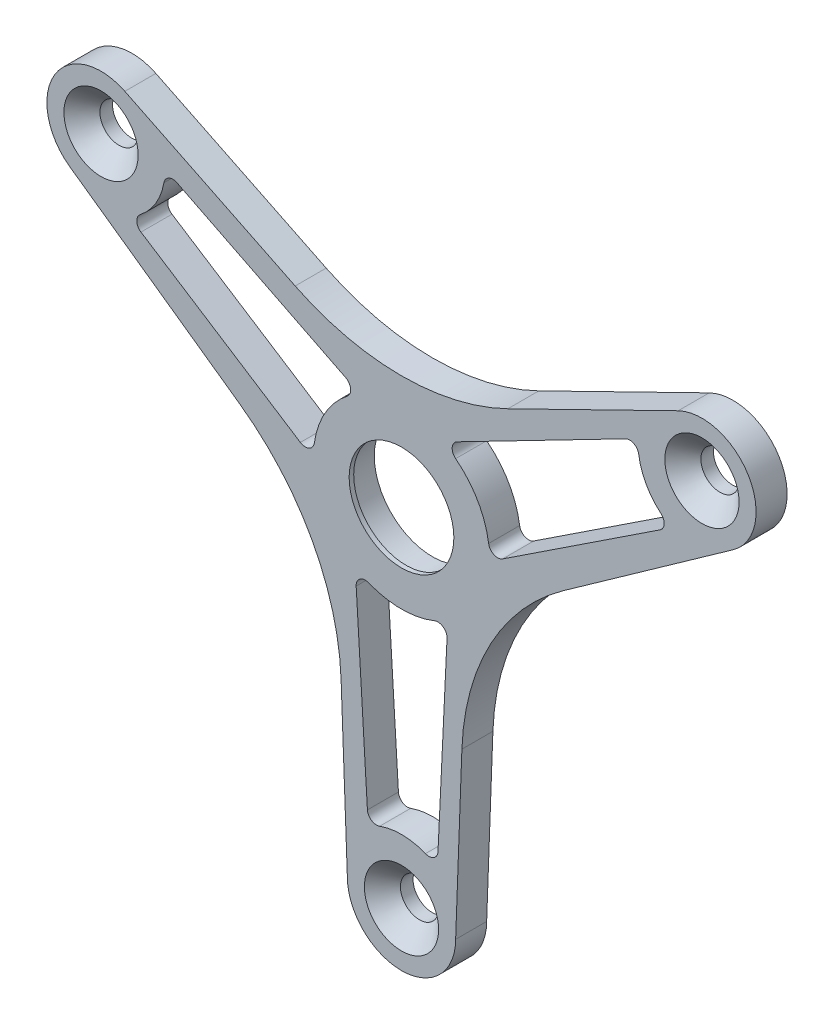
SolidWorks part; units mm, degrees
material "1060 合金"
ref_plane "前视基准面" through (0, 0, 0) normal (0, 0, 1) x (1, 0, 0)
ref_plane "上视基准面" through (0, 0, 0) normal (0, 1, 0) x (1, 0, 0)
ref_plane "右视基准面" through (0, 0, 0) normal (1, 0, 0) x (0, 0, -1)
sketch "草图1" plane through (0, 0, 0) normal (0, 0, 1) x (1, 0, 0)
  line L0 (-32.9393, 19.0175) -> (0, 0) construction
  line L1 (0, 0) -> (32.9393, 19.0175) construction
  line L2 (0, 0) -> (0, -38.035) construction
  line L3 (-30.3285, 24.3474) -> (-11.6571, 15.2016)
  line L4 (11.6571, 15.2016) -> (30.3285, 24.3474)
  line L5 (-36.371, 14.1752) -> (-17.7794, 0.9993)
  line L6 (-6.6205, -19.635) -> (-5.935, -38.035)
  line L7 (36.371, 14.1752) -> (17.7794, 0.9993)
  line L8 (6.6205, -19.635) -> (5.935, -38.035)
  circle A0 centre (0, 0) radius 5.74
  circle A1 centre (-32.9393, 19.0175) radius 2.095
  circle A2 centre (32.9393, 19.0175) radius 2.095
  circle A3 centre (0, -38.035) radius 2.095
  circle A4 centre (-32.9393, 19.0175) radius 5.935
  circle A5 centre (32.9393, 19.0175) radius 5.935
  circle A6 centre (0, -38.035) radius 5.935
  arc A7 (-11.6571, 15.2016) -> (11.6571, 15.2016) centre (0, 39) ccw
  arc A8 (-17.7794, 0.9993) -> (-6.6205, -19.635) centre (-33.1021, -20.6216) cw
  arc A9 (17.7794, 0.9993) -> (6.6205, -19.635) centre (33.1021, -20.6216) ccw
  dimension "D3" = 4.19
  dimension "D4" = 4.19
  dimension "D5" = 4.19
  dimension "D9" = 11.87
  dimension "D10" = 11.87
  dimension "D11" = 11.87
  dimension "D14" = 26.5
  dimension "D15" = 26.5
  dimension "D16" = 39
  dimension "D12" = 11.48
  dimension "D13" = 26.5
  dimension "D1" = 120
  dimension "D2" = 120
  dimension "D6" = 38.035
  dimension "D7" = 38.035
  dimension "D8" = 38.035
  dimension "D17" = 39
  dimension "D18" = 39
extrude "凸台-拉伸1" add sketch "草图1" along normal blind 3.4 contours A4 A1 | A5 A2 | A9 L7 A5 L4 A7 L3 A4 L5 A8 L6 A6 L8 A0 | A6 A3
sketch "草图2" plane through (0, 0, 3.4) normal (0, 0, 1) x (1, 0, 0)
  circle A0 centre (-32.9393, 19.0175) radius 4.07
  circle A1 centre (32.9393, 19.0175) radius 4.07
  circle A2 centre (0, -38.035) radius 4.07
  dimension "D1" = 8.14
  dimension "D2" = 8.14
  dimension "D3" = 8.14
sketch "草图3" plane through (0, 0, 0) normal (0, 0, -1) x (-1, 0, 0)
  circle A0 centre (0, 0) radius 6.38
  dimension "D1" = 12.76
extrude "切除-拉伸1" cut sketch "草图3" against normal blind 2.9
sketch "草图4" plane through (0, 0, 0) normal (0, 0, -1) x (-1, 0, 0)
  circle A0 centre (0, -38.035) radius 4.5
  circle A1 centre (32.9393, 19.0175) radius 4.5
  circle A2 centre (-32.9393, 19.0175) radius 4.5
  dimension "D1" = 9
  dimension "D2" = 9
  dimension "D3" = 9
extrude "凸台-拉伸3" add sketch "草图4" along normal blind 0.56
sketch "草图6" plane through (0, 0, -0.56) normal (0, 0, -1) x (-1, 0, 0)
  circle A0 centre (0, -38.035) radius 3.15
  dimension "D1" = 6.3
extrude "切除-拉伸2" cut sketch "草图6" against normal blind 0.6
sketch "草图7" plane through (0, 0, -0.56) normal (0, 0, -1) x (-1, 0, 0)
  circle A0 centre (-32.9393, 19.0175) radius 3.15
  dimension "D1" = 6.3
extrude "切除-拉伸3" cut sketch "草图7" against normal blind 0.6
sketch "草图8" plane through (0, 0, -0.56) normal (0, 0, -1) x (-1, 0, 0)
  circle A0 centre (32.9393, 19.0175) radius 3.15
  dimension "D1" = 6.3
extrude "切除-拉伸4" cut sketch "草图8" against normal blind 0.6
ref_plane "基准面1" through (0, 19.0175, 0) normal (0, -1, 0) x (-1, 0, 0)
sketch "草图9" plane through (0, 19.0175, 0) normal (0, -1, 0) x (-1, 0, 0)
  line L0 (30.8443, -3.4) -> (30.8443, 9.3358) construction
  line L1 (35.0343, -3.4) -> (35.0343, 9.3358) construction
  line L3 (35.0343, -3.4) -> (35.0343, -1.425)
  line L4 (35.0343, -1.425) -> (37.0093, -3.4)
  line L5 (37.0093, -3.4) -> (35.0343, -3.4)
  line L7 (32.9393, -3.4) -> (32.9393, 5.8602) construction
  dimension "D1" = 1.975
  dimension "D2" = 45
revolve "切除-旋转1" cut sketch "草图9" angle 360 about L7
ref_plane "基准面2" through (16.4696, -9.5087, 0) normal (-0.866, 0.5, 0) x (0, 0, 1)
sketch "草图10" plane through (16.4696, -9.5087, 0) normal (-0.866, 0.5, 0) x (0, 0, 1)
  line L0 (3.4, 35.0343) -> (3.4, 37.0093)
  line L1 (3.4, 37.0093) -> (1.425, 35.0343)
  line L2 (1.425, 35.0343) -> (3.4, 35.0343)
  line L5 (3.4, 32.9393) -> (0, 32.9393) construction
  dimension "D1" = 45
revolve "切除-旋转2" cut sketch "草图10" angle 360 about L5
sketch "草图11" plane through (16.4696, -9.5087, 0) normal (-0.866, 0.5, 0) x (0, 0, 1)
  line L0 (3.4, -30.8443) -> (3.4, -28.8693)
  line L1 (3.4, -28.8693) -> (1.425, -30.8443)
  line L2 (1.425, -30.8443) -> (3.4, -30.8443)
  line L7 (3.4, -32.9393) -> (0, -32.9393) construction
  dimension "D1" = 45
revolve "切除-旋转3" cut sketch "草图11" angle 360 about L7
sketch "草图12" plane through (0, 0, 0) normal (0, 0, -1) x (-1, 0, 0)
  line L0 (-32.9393, 19.0175) -> (0, 0) construction
  line L1 (-4.9914, -9.9209) -> (-4.0024, -30.6679)
  line L2 (3.7357, -30.5776) -> (4.9694, -9.9416)
  line L3 (-6.0961, 9.2831) -> (-24.5579, 18.8001)
  line L4 (-28.3489, 12.0536) -> (-11.0944, 0.6671)
  line L5 (11.0875, 0.6378) -> (28.5604, 11.8677)
  line L6 (24.6131, 18.5241) -> (6.1249, 9.2744)
  arc A6 (-3.6177, -8.9462) -> (3.5983, -8.954) centre (0, 0) ccw
  arc A7 (-2.6281, -31.5471) -> (2.3953, -31.4576) centre (0, -38.035) cw
  arc A8 (-4.0024, -30.6679) -> (-2.6281, -31.5471) centre (-3.0036, -30.6202) ccw
  arc A9 (2.3953, -31.4576) -> (3.7357, -30.5776) centre (2.7375, -30.518) ccw
  arc A10 (3.5983, -8.954) -> (4.9694, -9.9416) centre (3.9712, -9.8819) cw
  arc A11 (-4.9914, -9.9209) -> (-3.6177, -8.9462) centre (-3.9925, -9.8733) cw
  arc A12 (-6.0961, 9.2831) -> (-5.9388, 7.6061) centre (-6.5543, 8.3943) cw
  arc A13 (-24.5579, 18.8001) -> (-26.0065, 18.0496) centre (-25.0161, 17.9113) ccw
  arc A14 (-26.0065, 18.0496) -> (-28.4407, 13.6544) centre (-32.9393, 19.0175) cw
  arc A15 (-28.4407, 13.6544) -> (-28.3489, 12.0536) centre (-27.7981, 12.8882) ccw
  arc A16 (-9.5536, 1.3608) -> (-11.0944, 0.6671) centre (-10.5436, 1.5018) cw
  arc A17 (-5.9388, 7.6061) -> (-9.5536, 1.3608) centre (0, 0) ccw
  arc A18 (11.0875, 0.6378) -> (9.5565, 1.3401) centre (10.5468, 1.479) cw
  arc A19 (28.5604, 11.8677) -> (28.6346, 13.4975) centre (28.0197, 12.709) ccw
  arc A20 (28.6346, 13.4975) -> (26.0454, 17.8032) centre (32.9393, 19.0175) cw
  arc A21 (26.0454, 17.8032) -> (24.6131, 18.5241) centre (25.0606, 17.6297) ccw
  arc A22 (5.9552, 7.5933) -> (6.1249, 9.2744) centre (6.5724, 8.3801) cw
  arc A23 (9.5565, 1.3401) -> (5.9552, 7.5933) centre (0, 0) ccw
  point P52 (0, 0)
  dimension "D1" = 1
  dimension "D4" = 3
extrude "切除-拉伸5" cut sketch "草图12" against normal blind 10
